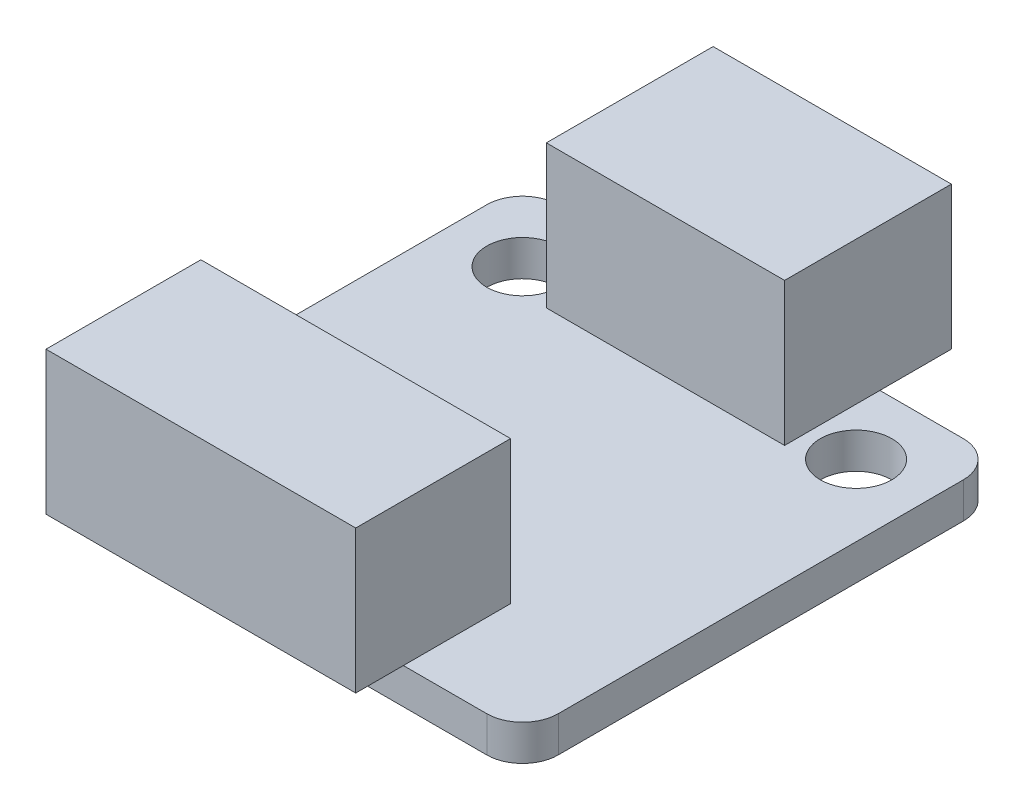
SolidWorks part; units mm, degrees
material "Custom Plastic"
ref_plane "Front Plane" through (0, 0, 0) normal (0, 0, 1) x (1, 0, 0)
ref_plane "Top Plane" through (0, 0, 0) normal (0, 1, 0) x (1, 0, 0)
ref_plane "Right Plane" through (0, 0, 0) normal (1, 0, 0) x (0, 0, -1)
sketch "Sketch1" plane through (0, 0, 0) normal (0, 1, 0) x (1, 0, 0)
  line L1 (10, -10) -> (-10, -10)
  line L2 (10, -10) -> (10, 10)
  line L3 (10, 10) -> (-10, 10)
  line L4 (-10, -10) -> (-10, 10)
  line L5 (10, -10) -> (-10, 10) construction
  line L6 (10, 10) -> (-10, -10) construction
  point P0 (0, 0)
  dimension "D1" = 20
extrude "Boss-Extrude1" add sketch "Sketch1" along normal blind 1.5
fillet "Fillet1" radius 1.5 4 edges at (10, 0.75, 10) (10, 0.75, -10) (-10, 0.75, 10) (-10, 0.75, -10)
sketch "Sketch2" plane through (0, 1.5, 0) normal (0, 1, 0) x (1, 0, 0)
  line L0 (-10, 8.5) -> (-10, -8.5) construction
  line L1 (8.5, 10) -> (-8.5, 10) construction
  line L2 (10, -8.5) -> (10, 8.5) construction
  circle A1 centre (7, 7) radius 1.5
  circle A2 centre (-7, 7) radius 1.5
  point P5 (-6.6666, 6.5736)
  point P8 (-8.5, 7.8219)
  point P15 (2.0451, 7.0517)
  dimension "D1" = 3
  dimension "D2" = 3
  dimension "D3" = 3
  dimension "D4" = 3
  dimension "D5" = 3
extrude "Cut-Extrude1" cut sketch "Sketch2" against normal up to surface (1.5 mm away) up to face at (0, 0, 0)
sketch "Sketch3" plane through (0, 1.5, 0) normal (0, 1, 0) x (1, 0, 0)
  line L0 (8.5, 10) -> (-8.5, 10) construction
  line L1 (5, 6) -> (-5, 6)
  line L2 (5, 6) -> (5, 13)
  line L3 (5, 13) -> (-5, 13)
  line L4 (-5, 6) -> (-5, 13)
  line L5 (5, 6) -> (-5, 13) construction
  line L6 (5, 13) -> (-5, 6) construction
  point P0 (0, 9.5)
  point P5 (0, 0)
  dimension "D1" = 7
  dimension "D2" = 10
  dimension "D3" = 3
extrude "Boss-Extrude2" add sketch "Sketch3" along normal blind 6
sketch "Sketch4" plane through (0, 1.5, 0) normal (0, 1, 0) x (1, 0, 0)
  line L0 (5, 6) -> (5, 10) construction
  line L1 (-8, -12) -> (5, -12)
  line L2 (-8, -12) -> (-8, -5.5)
  line L3 (-8, -5.5) -> (5, -5.5)
  line L4 (5, -12) -> (5, -5.5)
  line L5 (-8, -12) -> (5, -5.5) construction
  line L6 (-8, -5.5) -> (5, -12) construction
  line L7 (-8.5, -10) -> (8.5, -10) construction
  point P0 (-1.5, -8.75)
  dimension "D1" = 13
  dimension "D2" = 6.5
  dimension "D3" = 2
extrude "Boss-Extrude3" add sketch "Sketch4" along normal blind 6
